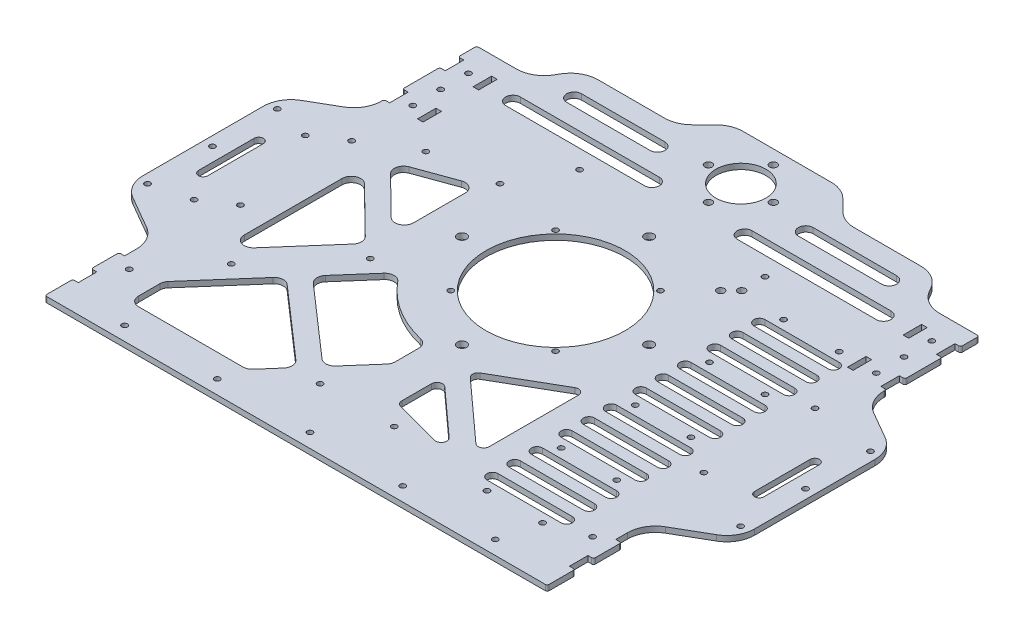
SolidWorks part; units mm, degrees
material "Thornel Mat VMA"
ref_plane "前视基准面" through (0, 0, 0) normal (0, 0, 1) x (1, 0, 0)
ref_plane "上视基准面" through (0, 0, 0) normal (0, 1, 0) x (1, 0, 0)
ref_plane "右视基准面" through (0, 0, 0) normal (1, 0, 0) x (0, 0, -1)
sketch "草图1" plane through (0, 0, 0) normal (0, 1, 0) x (1, 0, 0)
  line L0 (0, 0) -> (0, 125) construction
  line L1 (-135.5, -140) -> (135.5, -140)
  line L2 (-165, -66.2361) -> (-165, 15.9682)
  line L3 (114.5, 53) -> (114.5, 43)
  line L4 (165, -66.2361) -> (165, 15.9682)
  line L5 (0, 0) -> (0, -140) construction
  line L6 (135.5, -140) -> (135.5, -125)
  line L7 (132.5, -85) -> (165, -66.2361)
  line L8 (-165, -66.2361) -> (-132.5, -85)
  line L9 (-135.5, -100) -> (-135.5, -115)
  line L10 (135.5, -125) -> (132.5, -125)
  line L11 (132.5, -125) -> (132.5, -115)
  line L12 (132.5, -115) -> (135.5, -115)
  line L13 (135.5, -115) -> (135.5, -100)
  line L14 (-132.5, -115) -> (-135.5, -115)
  line L15 (-132.5, -125) -> (-132.5, -115)
  line L16 (-135.5, -125) -> (-132.5, -125)
  line L17 (-135.5, -125) -> (-135.5, -140)
  line L18 (135.5, -100) -> (132.5, -100)
  line L19 (132.5, -100) -> (132.5, -85)
  line L20 (-135.5, -100) -> (-132.5, -100)
  line L21 (-132.5, -100) -> (-132.5, -85)
  line L22 (125, 93) -> (125, -140) construction
  line L23 (-125, 93) -> (-125, -140) construction
  line L24 (95.685, 110) -> (105.5, 93)
  line L25 (105.5, 93) -> (135.5, 93)
  line L26 (-135.5, 93) -> (-105.5, 93)
  line L27 (-105.5, 93) -> (-95.685, 110)
  line L28 (-30, 125) -> (30, 125)
  line L29 (132.5, 83) -> (135.5, 83)
  line L30 (132.5, 83) -> (132.5, 73)
  line L31 (132.5, 73) -> (135.5, 73)
  line L32 (-135.5, 93) -> (-135.5, 83)
  line L33 (132.5, 53) -> (135.5, 53)
  line L34 (132.5, 53) -> (132.5, 43)
  line L35 (132.5, 43) -> (135.5, 43)
  line L36 (-135.5, 73) -> (-135.5, 53)
  line L37 (117.5, 43) -> (114.5, 43)
  line L38 (117.5, 53) -> (117.5, 43)
  line L39 (117.5, 53) -> (114.5, 53)
  line L40 (114.5, 83) -> (114.5, 73)
  line L41 (117.5, 73) -> (114.5, 73)
  line L42 (117.5, 83) -> (117.5, 73)
  line L43 (117.5, 83) -> (114.5, 83)
  line L44 (-117.5, 83) -> (-114.5, 83)
  line L45 (-117.5, 83) -> (-117.5, 73)
  line L46 (-117.5, 73) -> (-114.5, 73)
  line L47 (-114.5, 83) -> (-114.5, 73)
  line L48 (-117.5, 53) -> (-114.5, 53)
  line L49 (-117.5, 53) -> (-117.5, 43)
  line L50 (-117.5, 43) -> (-114.5, 43)
  line L51 (30, 125) -> (45, 110)
  line L52 (-132.5, 43) -> (-135.5, 43)
  line L53 (-132.5, 53) -> (-132.5, 43)
  line L54 (-132.5, 53) -> (-135.5, 53)
  line L55 (45, 110) -> (95.685, 110)
  line L56 (-132.5, 73) -> (-135.5, 73)
  line L57 (-132.5, 83) -> (-132.5, 73)
  line L58 (-132.5, 83) -> (-135.5, 83)
  line L59 (-114.5, 53) -> (-114.5, 43)
  line L60 (135.5, 93) -> (135.5, 83)
  line L61 (135.5, 73) -> (135.5, 53)
  line L62 (135.5, 43) -> (135.5, 33)
  line L63 (135.5, 33) -> (165, 15.9682)
  line L64 (-135.5, 43) -> (-135.5, 33)
  line L65 (-135.5, 33) -> (-165, 15.9682)
  line L66 (-30, 125) -> (-45, 110)
  line L67 (-45, 110) -> (-95.685, 110)
  line L68 (-165, -7.5) -> (165, -7.5) construction
  line L69 (-125, 63) -> (125, 63) construction
  line L70 (0, 0) -> (-100, 0) construction
  line L71 (-100, 30) -> (-100, -75) construction
  line L72 (-65, 35) -> (-65, -35) construction
  line L73 (-140, 5) -> (-140, -55) construction
  line L74 (-160, 9.866) -> (-160, -60.134) construction
  line L75 (160, 9.866) -> (160, -60.134) construction
  line L76 (-150, -40.134) -> (-150, -10.134) construction
  line L77 (-152.5, -40.134) -> (-152.5, -10.134)
  line L78 (-147.5, -40.134) -> (-147.5, -10.134)
  line L79 (-10, -63.7593) -> (-10, -76.5656)
  line L80 (-48.6301, -120) -> (-105, -120)
  line L81 (-110, -115) -> (-110, -103.4932)
  line L82 (-97.3448, 18.3635) -> (-76.7101, 25.8739)
  line L83 (-108.7629, -100.2006) -> (-82.3336, -69.9958)
  line L84 (-70, 21.1754) -> (-70, -6.6012)
  line L85 (-100, -75) -> (-65, -35) construction
  line L86 (-76.4062, -32.8498) -> (-101.2371, -61.2279)
  line L87 (-110, -57.9354) -> (-110, -5.1698)
  line L88 (-110, 13.7574) -> (-70, -25.5284) construction
  line L89 (-101.4965, -1.6026) -> (-76.6656, -25.99)
  line L90 (-99.1382, 10.0978) -> (-78.5035, -10.1685)
  line L91 (-106.4965, 17.3246) -> (-66.4965, -21.9611) construction
  line L92 (-113.5035, 10.1901) -> (-73.5035, -29.0956) construction
  line L93 (-10, -120) -> (-75.7486, -62.47) construction
  line L94 (-31.0643, -94.9249) -> (-68.6932, -61.9996)
  line L95 (-37.6494, -102.4506) -> (-75.2782, -69.5254)
  line L96 (-69.1635, -54.9442) -> (-54.4772, -38.1599)
  line L97 (-6.7075, -116.2371) -> (-72.456, -58.7071) construction
  line L98 (-13.2925, -123.7629) -> (-79.0411, -66.2329) construction
  line L99 (-85, 95) -> (-40, 95) construction
  line L100 (-85, 99) -> (-40, 99)
  line L101 (-85, 91) -> (-40, 91)
  line L102 (-100, 77) -> (-25, 77) construction
  line L103 (-100, 81) -> (-25, 81)
  line L104 (-100, 73) -> (-25, 73)
  line L105 (85, 95) -> (40, 95) construction
  line L106 (85, 99) -> (40, 99)
  line L107 (85, 91) -> (40, 91)
  line L108 (100, 77) -> (25, 77) construction
  line L109 (100, 81) -> (25, 81)
  line L110 (100, 73) -> (25, 73)
  line L111 (75, 48) -> (105, 48) construction
  line L112 (105, 48) -> (105, 8) construction
  line L113 (70, 40) -> (110, 40) construction
  line L114 (70, 43) -> (110, 43)
  line L115 (70, 28) -> (110, 28) construction
  line L116 (70, 31) -> (110, 31)
  line L117 (70, 37) -> (110, 37)
  line L118 (90, 48) -> (90, 40) construction
  line L119 (90, 40) -> (90, -104) construction
  line L120 (70, 25) -> (110, 25)
  line L121 (70, 16) -> (110, 16) construction
  line L122 (70, 19) -> (110, 19)
  line L123 (70, 13) -> (110, 13)
  line L124 (70, 0) -> (110, 0) construction
  line L125 (-44.8672, -118.2925) -> (-37.179, -109.506)
  line L126 (-24.0089, -94.4545) -> (-11.2371, -79.8582)
  line L127 (70, 3) -> (110, 3)
  line L128 (70, -3) -> (110, -3)
  line L129 (70, -12) -> (110, -12) construction
  line L130 (70, -9) -> (110, -9)
  line L131 (70, -15) -> (110, -15)
  line L132 (70, -24) -> (110, -24) construction
  line L133 (70, -21) -> (110, -21)
  line L134 (70, -27) -> (110, -27)
  line L135 (70, -40) -> (110, -40) construction
  line L136 (70, -37) -> (110, -37)
  line L137 (70, -43) -> (110, -43)
  line L138 (70, -52) -> (110, -52) construction
  line L139 (70, -49) -> (110, -49)
  line L140 (70, -55) -> (110, -55)
  line L141 (70, -64) -> (110, -64) construction
  line L142 (70, -61) -> (110, -61)
  line L143 (70, -67) -> (110, -67)
  line L144 (70, -80) -> (110, -80) construction
  line L145 (70, -77) -> (110, -77)
  line L146 (70, -83) -> (110, -83)
  line L147 (70, -92) -> (110, -92) construction
  line L148 (70, -89) -> (110, -89)
  line L149 (70, -95) -> (110, -95)
  line L150 (70, -104) -> (110, -104) construction
  line L151 (70, -101) -> (110, -101)
  line L152 (70, -107) -> (110, -107)
  line L153 (50.5, -40.0981) -> (18.1131, -58.7967)
  line L154 (10, -63.4808) -> (55, -104.2466) construction
  line L155 (-20, -107) -> (20, -107) construction
  line L156 (17.5989, -63.6181) -> (49.9859, -92.9577)
  line L157 (10, -76.9931) -> (10, -92.9254)
  line L158 (12.2235, -95.8232) -> (37.1975, -102.5149)
  line L159 (55, -90.7343) -> (55, -42.6962)
  line L160 (0, 0) -> (44.5477, 44.5477) construction
  line L161 (50.2046, 50.2046) -> (44.5477, 44.5477) construction
  line L162 (15.0141, -74.7697) -> (39.9881, -97.3938)
  line L163 (13.3569, -59.7752) -> (58.3569, -100.541) construction
  line L164 (6.6431, -67.1863) -> (51.6431, -107.9522) construction
  line L165 (150, -40.134) -> (150, -10.134) construction
  line L166 (152.5, -40.134) -> (152.5, -10.134)
  line L167 (147.5, -40.134) -> (147.5, -10.134)
  circle A0 centre (125, 78) radius 1.5
  circle A1 centre (0, 100) radius 13.5
  circle A2 centre (0, 0) radius 50.5 construction
  circle A3 centre (0, 100) radius 17.5 construction
  circle A4 centre (0, 117.5) radius 2
  circle A5 centre (17.5, 100) radius 2
  circle A6 centre (0, 82.5) radius 2
  circle A7 centre (-17.5, 100) radius 2
  circle A8 centre (44.5477, 44.5477) radius 2
  circle A9 centre (100, -132.5) radius 1.5 construction
  circle A10 centre (50, -132.5) radius 1.5 construction
  circle A11 centre (0, -132.5) radius 1.5 construction
  circle A12 centre (-50, -132.5) radius 1.5 construction
  circle A13 centre (-100, -132.5) radius 1.5 construction
  circle A14 centre (50.2046, 50.2046) radius 2
  arc A15 (70, 31) -> (70, 25) centre (70, 28) ccw
  circle A16 centre (100, -132.5) radius 1.5
  circle A17 centre (50, -132.5) radius 1.5
  circle A18 centre (0, -132.5) radius 1.5
  circle A19 centre (-50, -132.5) radius 1.5
  circle A20 centre (-100, -132.5) radius 1.5
  arc A21 (110, 25) -> (110, 31) centre (110, 28) ccw
  circle A22 centre (125, -105) radius 1.5
  circle A23 centre (125, -45) radius 1.5
  circle A24 centre (125, 15) radius 1.5
  circle A25 centre (-125, 78) radius 1.5
  circle A26 centre (-125, 15) radius 1.5
  circle A27 centre (-125, -45) radius 1.5
  circle A28 centre (-125, -105) radius 1.5
  circle A29 centre (125, 75) radius 1.5 [skipped]
  circle A30 centre (125, 48) radius 1.5
  circle A31 centre (-125, 48) radius 1.5
  circle A32 centre (0, 0) radius 37.5
  circle A33 centre (50.5, 0) radius 2.5
  circle A34 centre (0, -50.5) radius 2.5
  circle A35 centre (-50.5, 0) radius 2.5
  circle A36 centre (0, 50.5) radius 2.5
  circle A37 centre (125, 63) radius 1.5
  circle A38 centre (-125, 63) radius 1.5
  circle A39 centre (-100, 30) radius 1.5
  circle A40 centre (50, 63) radius 1.5
  circle A41 centre (-50, 63) radius 1.5
  circle A42 centre (-100, -75) radius 1.5
  circle A43 centre (-65, 35) radius 1.5
  circle A44 centre (-65, -35) radius 1.5
  circle A45 centre (-140, 5) radius 1.5
  circle A46 centre (-140, -55) radius 1.5
  circle A47 centre (-160, 9.866) radius 1.5
  circle A48 centre (-160, -25.134) radius 1.5
  circle A49 centre (-160, -60.134) radius 1.5
  circle A50 centre (160, 9.866) radius 1.5
  circle A51 centre (160, -60.134) radius 1.5
  circle A52 centre (160, -25.134) radius 1.5
  arc A53 (-152.5, -40.134) -> (-147.5, -40.134) centre (-150, -40.134) ccw
  arc A54 (-147.5, -10.134) -> (-152.5, -10.134) centre (-150, -10.134) ccw
  arc A55 (-46.843, -38.2881) -> (-13.855, -58.8922) centre (0, 0) ccw
  arc A56 (-10, -63.7593) -> (-13.855, -58.8922) centre (-15, -63.7593) ccw
  arc A57 (-54.4772, -38.1599) -> (-46.843, -38.2881) centre (-50.7144, -41.4524) cw
  arc A58 (-75.2782, -69.5254) -> (-82.3336, -69.9958) centre (-78.5707, -73.2883) ccw
  arc A59 (-68.6932, -61.9996) -> (-69.1635, -54.9442) centre (-65.4006, -58.2368) cw
  arc A60 (-11.2371, -79.8582) -> (-10, -76.5656) centre (-15, -76.5656) ccw
  arc A61 (-44.8672, -118.2925) -> (-48.6301, -120) centre (-48.6301, -115) cw
  arc A62 (-105, -120) -> (-110, -115) centre (-105, -115) cw
  arc A63 (-110, -103.4932) -> (-108.7629, -100.2006) centre (-105, -103.4932) cw
  arc A64 (-101.2371, -61.2279) -> (-110, -57.9354) centre (-105, -57.9354) cw
  arc A65 (-110, -5.1698) -> (-101.4965, -1.6026) centre (-105, -5.1698) cw
  arc A66 (-76.4062, -32.8498) -> (-76.6656, -25.99) centre (-80.1691, -29.5573) ccw
  arc A67 (-76.7101, 25.8739) -> (-70, 21.1754) centre (-75, 21.1754) cw
  arc A68 (-78.5035, -10.1685) -> (-70, -6.6012) centre (-75, -6.6012) ccw
  arc A69 (-99.1382, 10.0978) -> (-97.3448, 18.3635) centre (-95.6347, 13.665) cw
  arc A70 (-85, 99) -> (-85, 91) centre (-85, 95) ccw
  arc A71 (-40, 91) -> (-40, 99) centre (-40, 95) ccw
  arc A72 (-100, 81) -> (-100, 73) centre (-100, 77) ccw
  arc A73 (-25, 73) -> (-25, 81) centre (-25, 77) ccw
  arc A74 (85, 99) -> (85, 91) centre (85, 95) cw
  arc A75 (40, 91) -> (40, 99) centre (40, 95) cw
  arc A76 (100, 81) -> (100, 73) centre (100, 77) cw
  arc A77 (25, 73) -> (25, 81) centre (25, 77) cw
  circle A78 centre (0, 0) radius 40 construction
  circle A79 centre (28.2843, -28.2843) radius 1.5
  circle A80 centre (-28.2843, -28.2843) radius 1.5
  circle A81 centre (-28.2843, 28.2843) radius 1.5
  circle A82 centre (28.2843, 28.2843) radius 1.5
  circle A83 centre (105, 48) radius 1.5
  circle A84 centre (75, 48) radius 1.5
  circle A85 centre (75, 8) radius 1.5
  circle A86 centre (75, -32) radius 1.5
  circle A87 centre (75, -72) radius 1.5
  circle A88 centre (75, -112) radius 1.5
  circle A89 centre (105, 8) radius 1.5
  circle A90 centre (105, -32) radius 1.5
  circle A91 centre (105, -72) radius 1.5
  circle A92 centre (105, -112) radius 1.5
  arc A93 (70, 43) -> (70, 37) centre (70, 40) ccw
  arc A94 (110, 37) -> (110, 43) centre (110, 40) ccw
  arc A95 (70, 19) -> (70, 13) centre (70, 16) ccw
  arc A96 (110, 13) -> (110, 19) centre (110, 16) ccw
  arc A97 (70, 3) -> (70, -3) centre (70, 0) ccw
  arc A98 (110, -3) -> (110, 3) centre (110, 0) ccw
  arc A99 (70, -9) -> (70, -15) centre (70, -12) ccw
  arc A100 (110, -15) -> (110, -9) centre (110, -12) ccw
  arc A101 (70, -21) -> (70, -27) centre (70, -24) ccw
  arc A102 (110, -27) -> (110, -21) centre (110, -24) ccw
  arc A103 (70, -37) -> (70, -43) centre (70, -40) ccw
  arc A104 (110, -43) -> (110, -37) centre (110, -40) ccw
  arc A105 (70, -49) -> (70, -55) centre (70, -52) ccw
  arc A106 (110, -55) -> (110, -49) centre (110, -52) ccw
  arc A107 (70, -61) -> (70, -67) centre (70, -64) ccw
  arc A108 (110, -67) -> (110, -61) centre (110, -64) ccw
  arc A109 (70, -77) -> (70, -83) centre (70, -80) ccw
  arc A110 (110, -83) -> (110, -77) centre (110, -80) ccw
  arc A111 (70, -89) -> (70, -95) centre (70, -92) ccw
  arc A112 (110, -95) -> (110, -89) centre (110, -92) ccw
  arc A113 (70, -101) -> (70, -107) centre (70, -104) ccw
  arc A114 (110, -107) -> (110, -101) centre (110, -104) ccw
  arc A117 (-37.6494, -102.4506) -> (-37.179, -109.506) centre (-40.9419, -106.2135) cw
  arc A118 (-31.0643, -94.9249) -> (-24.0089, -94.4545) centre (-27.7718, -91.162) ccw
  circle A119 centre (20, -107) radius 1.5
  circle A120 centre (-20, -107) radius 1.5
  arc A121 (10, -92.9254) -> (12.2235, -95.8232) centre (13, -92.9254) ccw
  arc A122 (10, -76.9931) -> (15.0141, -74.7697) centre (13, -76.9931) cw
  arc A123 (50.5, -40.0981) -> (55, -42.6962) centre (52, -42.6962) cw
  arc A124 (18.1131, -58.7967) -> (17.5989, -63.6181) centre (19.6131, -61.3948) ccw
  arc A125 (49.9859, -92.9577) -> (55, -90.7343) centre (52, -90.7343) ccw
  arc A126 (37.1975, -102.5149) -> (39.9881, -97.3938) centre (37.9739, -99.6171) ccw
  arc A127 (152.5, -40.134) -> (147.5, -40.134) centre (150, -40.134) cw
  arc A128 (147.5, -10.134) -> (152.5, -10.134) centre (150, -10.134) cw
  point P0 (0, 0)
  point P21 (132.5, -120)
  point P69 (0, 125)
  point P141 (0, 0)
  point P146 (0, 0)
  point P155 (-65, 0)
  point P171 (-165, -25.134)
  point P179 (-150, -25.134)
  point P229 (-110, -71.2426)
  point P242 (-62.5, 95)
  point P248 (-62.5, 77)
  point P256 (62.5, 95)
  point P263 (62.5, 77)
  point P280 (0, 0)
  point P282 (90, 40)
  point P310 (90, 28)
  point P316 (90, 16)
  point P327 (90, 0)
  point P334 (90, -12)
  point P340 (90, -24)
  point P349 (90, -40)
  point P355 (90, -52)
  point P361 (90, -64)
  point P370 (90, -80)
  point P376 (90, -92)
  point P382 (90, -104)
  point P391 (-27.3014, -98.2174)
  point P394 (0, -107)
  point P412 (10, -95.2274)
  point P415 (10, -70.2274)
  point P418 (55, -37.5)
  point P423 (55, -97.5)
  point P428 (150, -25.134)
  dimension "D4" = 100
  dimension "D5" = 75
  dimension "D6" = 27
  dimension "D7" = 35
  dimension "D8" = 4
  dimension "D14" = 35
  dimension "D18" = 188
  dimension "D25" = 30
  dimension "D22" = 5
  dimension "D33" = 45
  dimension "D36" = 101
  dimension "D38" = 5
  dimension "D40" = 15
  dimension "D41" = 100
  dimension "D42" = 3
  dimension "D48" = 3
  dimension "D51" = 5
  dimension "D52" = 3
  dimension "D55" = 2.5
  dimension "D62" = 10
  dimension "D63" = 5
  dimension "D71" = 5
  dimension "D72" = 4
  dimension "D73" = 4
  dimension "D80" = 80
  dimension "D81" = 3
  dimension "D83" = 3
  dimension "D90" = 3
  dimension "D97" = 5
  dimension "D100" = 3
  dimension "D110" = 3
  dimension "D112" = 3
  dimension "D113" = 5
  dimension "D116" = 4
  dimension "D93" = 12
  dimension "D2" = 330
  dimension "D3" = 140
  dimension "D9" = 271
  dimension "D10" = 3
  dimension "D11" = 15
  dimension "D12" = 10
  dimension "D13" = 15
  dimension "D16" = 60
  dimension "D17" = 25
  dimension "D19" = 15
  dimension "D20" = 10
  dimension "D21" = 20
  dimension "D23" = 7.5
  dimension "D24" = 3
  dimension "D26" = 15
  dimension "D27" = 10
  dimension "D28" = 60
  dimension "D29" = 60
  dimension "D30" = 3
  dimension "D31" = 30
  dimension "D32" = 60
  dimension "D34" = 30
  dimension "D35" = 15
  dimension "D39" = 7.5
  dimension "D43" = 70
  dimension "D44" = 65
  dimension "D45" = 100
  dimension "D46" = 30
  dimension "D47" = 75
  dimension "D49" = 15
  dimension "D50" = 60
  dimension "D53" = 70
  dimension "D54" = 5
  dimension "D56" = 10
  dimension "D57" = 30
  dimension "D58" = 10
  dimension "D59" = 20
  dimension "D60" = 15
  dimension "D61" = 10
  dimension "D64" = 20
  dimension "D65" = 70
  dimension "D66" = 85
  dimension "D74" = 10
  dimension "D75" = 10
  dimension "D76" = 40
  dimension "D77" = 25
  dimension "D78" = 75
  dimension "D79" = 45
  dimension "D82" = 4
  dimension "D84" = 15
  dimension "D85" = 20
  dimension "D86" = 2
  dimension "D87" = 5
  dimension "D88" = 30
  dimension "D89" = 40
  dimension "D91" = 40
  dimension "D92" = 8
  dimension "D94" = 12
  dimension "D96" = 60
  dimension "D98" = 40
  dimension "D99" = 33
  dimension "D101" = 60
  dimension "D102" = 35
  dimension "D103" = 20
  dimension "D104" = 30
  dimension "D105" = 75
  dimension "D108" = 60
  dimension "D109" = 25
  dimension "D111" = 7.5
  dimension "D114" = 63
  dimension "D115" = 45
  dimension "D117" = 8
  dimension "D118" = 16
  dimension "D67" = 5
  dimension "D68" = 5
  dimension "D69" = 5
  dimension "D70" = 5
  dimension "D106" = 5
  dimension "D107" = 5
  dimension "D15" = 4
  dimension "D95" = 4
  dimension "D37" = 4
extrude "凸台-拉伸1" add sketch "草图1" along normal blind 3
fillet "圆角1" radius 15 16 edges at (-105.5, 1.5, -93) (-95.685, 1.5, -110) (105.5, 1.5, -93) (95.685, 1.5, -110) (-45, 1.5, -110) (45, 1.5, -110) (30, 1.5, -125) (-30, 1.5, -125) (-165, 1.5, -15.9682) (-135.5, 1.5, -33) (-165, 1.5, 66.2361) (-132.5, 1.5, 85) (135.5, 1.5, -33) (165, 1.5, -15.9682) (165, 1.5, 66.2361) (132.5, 1.5, 85)
fillet "圆角2" radius 1 18 edges at (-135.5, 1.5, 140) (-135.5, 1.5, 125) (-135.5, 1.5, 115) (-135.5, 1.5, 100) (135.5, 1.5, 100) (135.5, 1.5, 140) (135.5, 1.5, 125) (135.5, 1.5, 115) (-135.5, 1.5, -43) (-135.5, 1.5, -53) (-135.5, 1.5, -73) (-135.5, 1.5, -83) (-135.5, 1.5, -93) (135.5, 1.5, -93) (135.5, 1.5, -83) (135.5, 1.5, -73) (135.5, 1.5, -53) (135.5, 1.5, -43)
